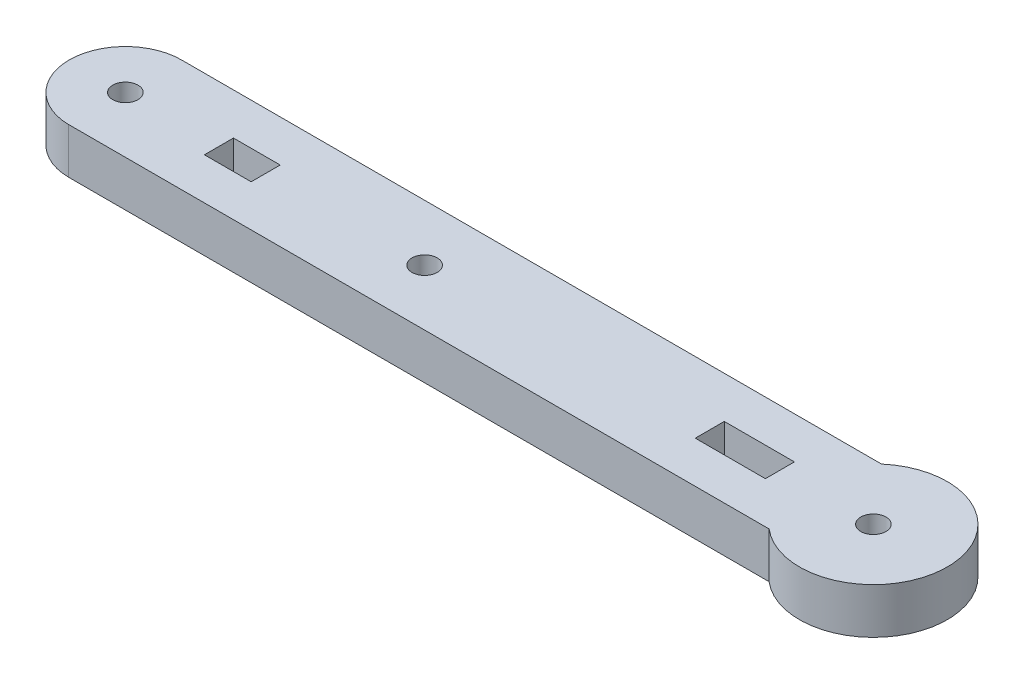
SolidWorks part; units mm, degrees
ref_plane "Front Plane" through (0, 0, 0) normal (0, 0, 1) x (1, 0, 0)
ref_plane "Top Plane" through (0, 0, 0) normal (0, 1, 0) x (1, 0, 0)
ref_plane "Right Plane" through (0, 0, 0) normal (1, 0, 0) x (0, 0, -1)
sketch "Sketch1" plane through (0, 0, 0) normal (0, 1, 0) x (1, 0, 0)
  line L0 (22.2544, 0.4676) -> (24.203, 0.4675) construction
  line L2 (19.8864, -3.4371) -> (-28.7899, -3.4368)
  line L3 (-28.7425, 4.3721) -> (19.8863, 4.3721)
  line L5 (-22.2425, 1.4436) -> (-22.2425, 1.4762)
  line L6 (-22.2425, 1.4762) -> (-18.9945, 1.4762)
  line L7 (-18.9945, 1.4762) -> (-18.9945, 1.4436)
  line L8 (-18.9945, 1.4436) -> (-18.9945, -0.5087)
  line L9 (-18.9945, -0.5087) -> (-18.9945, -0.5411)
  line L10 (-18.9945, -0.5411) -> (-22.2425, -0.5411)
  line L11 (-22.2425, -0.5411) -> (-22.2425, -0.5087)
  line L12 (-22.2425, -0.5087) -> (-22.2425, 1.4436)
  line L13 (11.8609, 1.4762) -> (16.7328, 1.4762)
  line L14 (16.7328, 1.4762) -> (16.7328, -0.5411)
  line L15 (16.7328, -0.5411) -> (11.8609, -0.5411)
  line L16 (11.8609, -0.5411) -> (11.8609, 1.4762)
  arc A0 (-28.7425, 4.3721) -> (-28.7899, -3.4368) centre (-28.7425, 0.4675) ccw
  arc A1 (19.8864, -3.4371) -> (19.8863, 4.3721) centre (23.2287, 0.4675) ccw
  circle A2 centre (-28.7425, 0.4675) radius 0.8763
  circle A3 centre (-7.9516, 0.4675) radius 0.8763
  circle A4 centre (23.2287, 0.4675) radius 0.8763
  point P2 (-7.9516, 0.4675)
  dimension "D1" = 1.7526
extrude "Boss-Extrude1" add sketch "Sketch1" along normal blind 3.175
